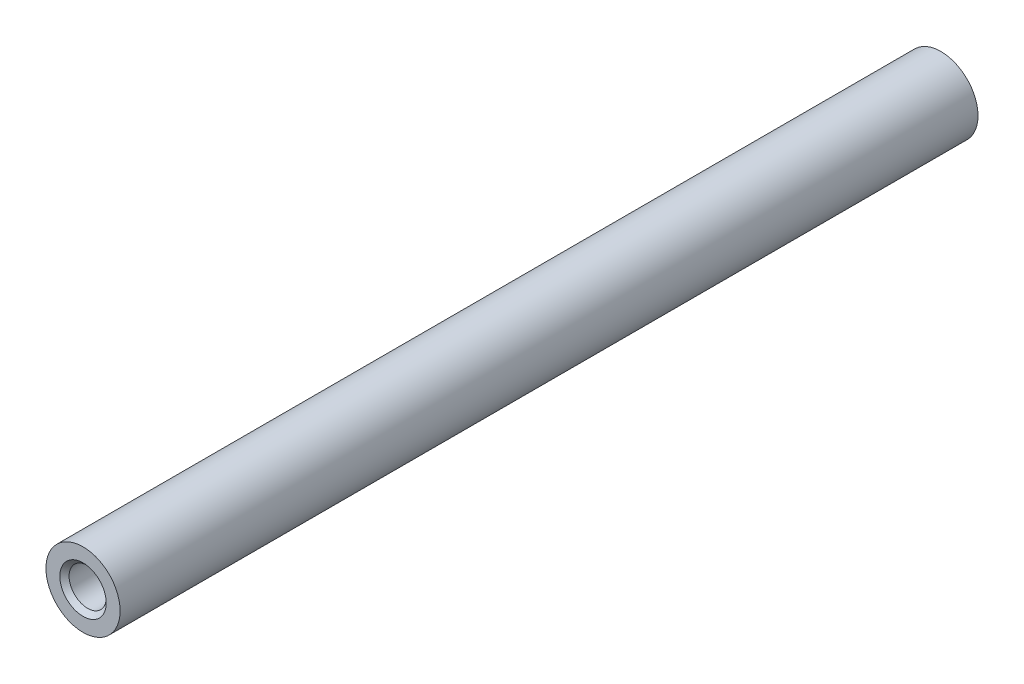
SolidWorks part; units mm, degrees
material "1.0545 (S355N)"
ref_plane "Płaszczyzna przednia" through (0, 0, 0) normal (0, 0, 1) x (1, 0, 0)
ref_plane "Płaszczyzna górna" through (0, 0, 0) normal (0, 1, 0) x (1, 0, 0)
ref_plane "Płaszczyzna prawa" through (0, 0, 0) normal (1, 0, 0) x (0, 0, -1)
sketch "Szkic1" plane through (0, 0, 0) normal (0, 0, 1) x (1, 0, 0)
  circle A0 centre (0, 0) radius 8
  circle A1 centre (0, 0) radius 4
  dimension "D1" = 4
  dimension "D2" = 16
extrude "Dodanie-wyciągnięcie1" add sketch "Szkic1" along normal mid plane 185
sketch "Szkic2" plane through (0, 0, -92.5) normal (0, 0, -1) x (-1, 0, 0)
  circle A0 centre (0, 0) radius 5
  circle A1 centre (0, 0) radius 4 construction
  dimension "D1" = 1
extrude "Wytnij-wyciągnięcie1" cut sketch "Szkic2" against normal blind 30
chamfer "Sfazowanie1" distance 1 angle 45 1 edges at (4, 0, 92.5)
